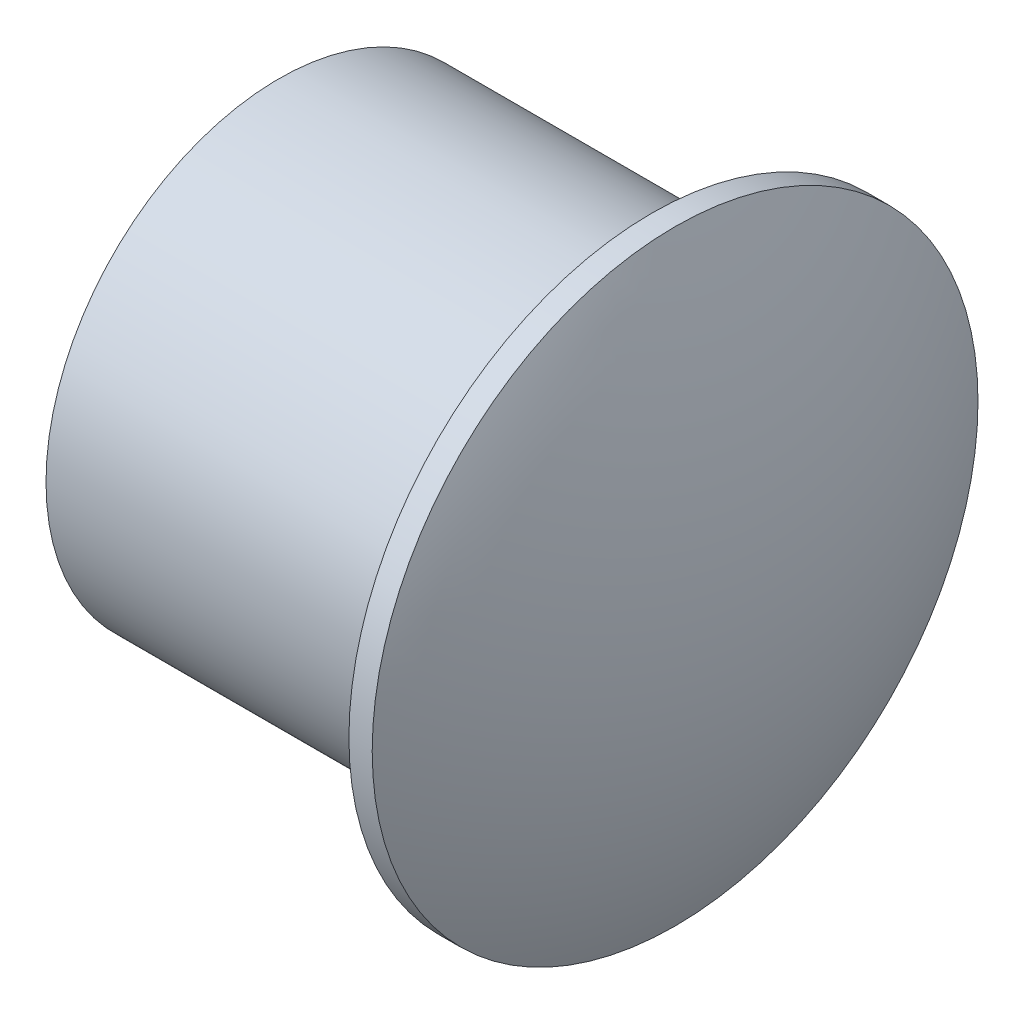
SolidWorks part; units mm, degrees
ref_plane "Front Plane" through (0, 0, 0) normal (0, 0, 1) x (1, 0, 0)
ref_plane "Top Plane" through (0, 0, 0) normal (0, 1, 0) x (1, 0, 0)
ref_plane "Right Plane" through (0, 0, 0) normal (1, 0, 0) x (0, 0, -1)
sketch "Sketch1" plane through (0, 0, 0) normal (0, 0, 1) x (1, 0, 0)
  line L0 (0, 0) -> (0, 10)
  line L1 (0, 10) -> (16, 10)
  line L2 (16, 10) -> (16, 13)
  line L3 (16, 13) -> (17, 13)
  line L4 (0, 0) -> (20, 0)
  arc A0 (20, 0) -> (17, 13) centre (-9.6667, 0) ccw
  point P8 (20, 17.4026)
  dimension "D1" = 10
  dimension "D2" = 20
  dimension "D3" = 16
  dimension "D4" = 3
  dimension "D5" = 1
revolve "Revolve1" add sketch "Sketch1" angle 360 about L4
